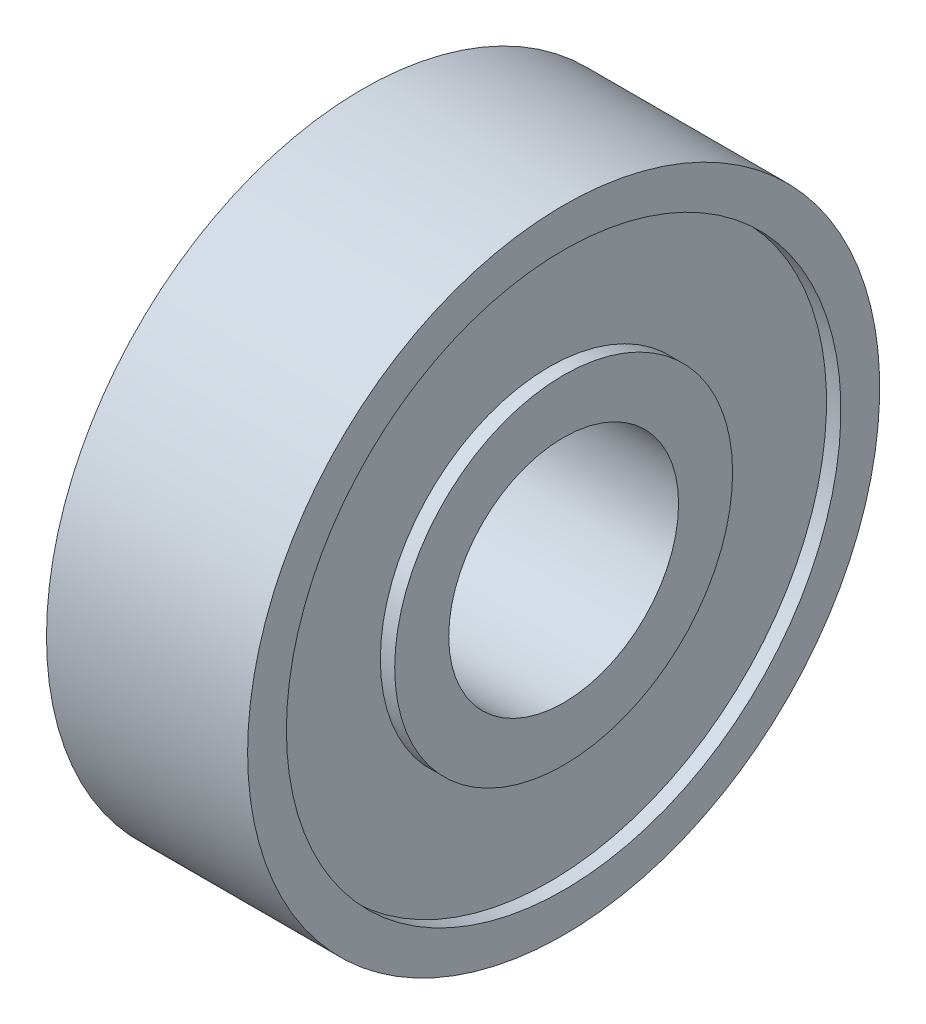
SolidWorks part; units mm, degrees
ref_plane "Front Plane" through (0, 0, 0) normal (0, 0, 1) x (1, 0, 0)
ref_plane "Top Plane" through (0, 0, 0) normal (0, 1, 0) x (1, 0, 0)
ref_plane "Right Plane" through (0, 0, 0) normal (1, 0, 0) x (0, 0, -1)
sketch "Sketch2" plane through (0, 0, 0) normal (0, 1, 0) x (1, 0, 0)
  line L0 (0, 0) -> (0, 18.219) construction
  line L1 (0, 0) -> (28.0939, 0) construction
  line L2 (3, 9.65) -> (3.5, 9.65)
  line L3 (-3.5, 11) -> (3.5, 11)
  line L4 (-3.5, 9.65) -> (-3.5, 5.88) construction
  line L5 (3, 5.88) -> (3.5, 5.88)
  line L6 (3.5, 11) -> (3.5, 9.65)
  line L7 (-3, 9.65) -> (3, 9.65) construction
  line L8 (-3.5, 5.88) -> (-3.5, 4)
  line L9 (-3, 5.88) -> (3, 5.88) construction
  line L10 (3, 9.65) -> (3, 5.88)
  line L11 (3.5, 9.65) -> (3.5, 5.88) construction
  line L12 (-3, 9.65) -> (-3, 5.88)
  line L13 (-3.5, 4) -> (3.5, 4)
  line L14 (3.5, 5.88) -> (3.5, 4)
  line L15 (-3.5, 11) -> (-3.5, 9.65)
  line L16 (-3, 5.88) -> (-3.5, 5.88)
  line L17 (-3, 9.65) -> (-3.5, 9.65)
  point P17 (0, 5.88)
  point P18 (0, 9.65)
  point P19 (0, 4)
  point P20 (0, 11)
  dimension "D1" = 4
  dimension "D2" = 3.5
  dimension "D3" = 0.5
  dimension "D4" = 1.35
  dimension "D5" = 1.88
  dimension "D6" = 11
revolve "Revolve2" add sketch "Sketch2" angle 360 about L1
ref_plane "Plane1" through (0, 0, 0) normal (1, 0, 0) x (0, 0, -1)
